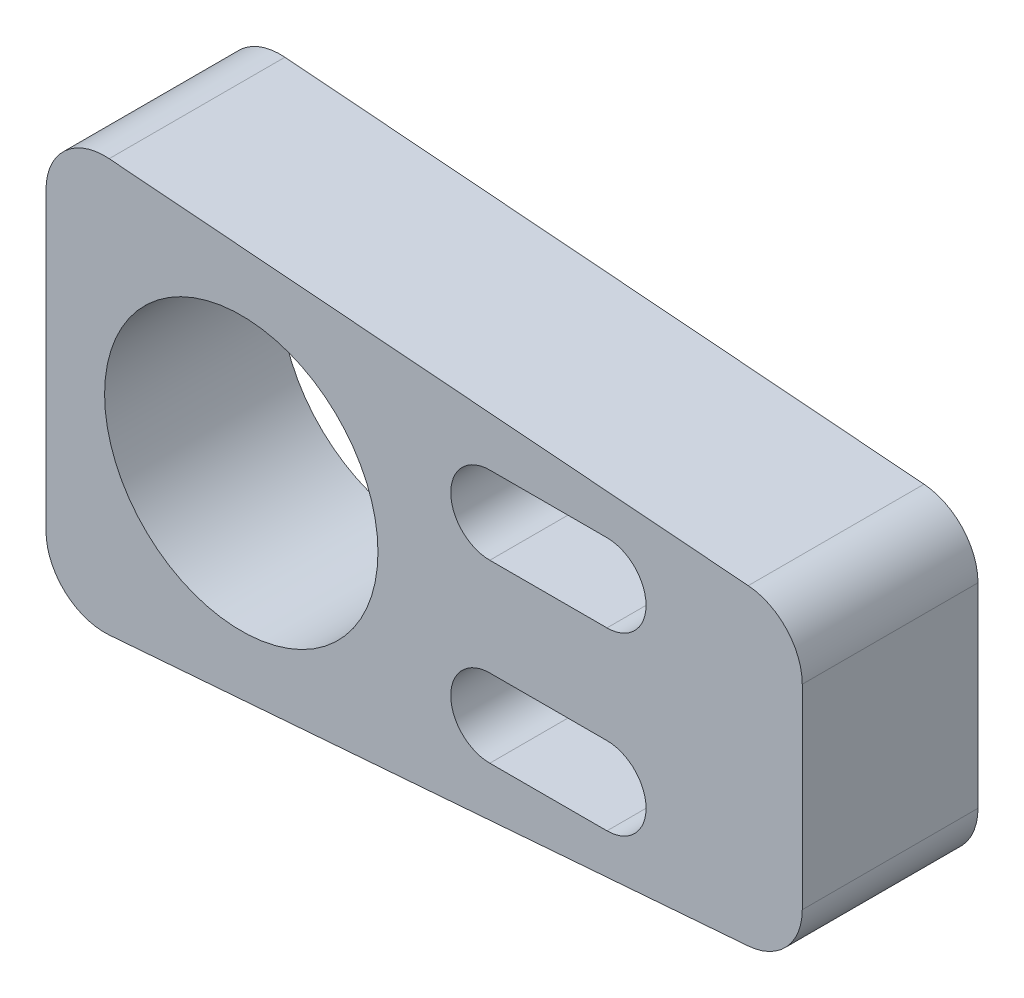
SolidWorks part; units mm, degrees
ref_plane "Front Plane" through (0, 0, 0) normal (0, 0, 1) x (1, 0, 0)
ref_plane "Top Plane" through (0, 0, 0) normal (0, 1, 0) x (1, 0, 0)
ref_plane "Right Plane" through (0, 0, 0) normal (1, 0, 0) x (0, 0, -1)
sketch "Sketch1" plane through (0, 0, 0) normal (0, 0, 1) x (1, 0, 0)
  line L1 (-114.4485, -4.5) -> (-120.4485, -4.5) construction
  line L2 (-139.9414, -10.5624) -> (-107.2135, -7.9908)
  line L3 (-143.1764, -7.5716) -> (-143.1764, 7.5716)
  line L4 (-139.9414, 10.5624) -> (-107.2135, 7.9908)
  line L5 (-104.4485, -5) -> (-104.4485, 5)
  line L8 (-114.4485, -6.5) -> (-120.4485, -6.5)
  line L9 (-114.4485, -2.5) -> (-120.4485, -2.5)
  line L10 (-114.4485, 4.5) -> (-120.4485, 4.5) construction
  line L11 (-114.4485, 2.5) -> (-120.4485, 2.5)
  line L12 (-114.4485, 6.5) -> (-120.4485, 6.5)
  arc A1 (-114.4485, -6.5) -> (-114.4485, -2.5) centre (-114.4485, -4.5) ccw
  arc A2 (-120.4485, -2.5) -> (-120.4485, -6.5) centre (-120.4485, -4.5) ccw
  arc A3 (-114.4485, 2.5) -> (-114.4485, 6.5) centre (-114.4485, 4.5) ccw
  arc A4 (-120.4485, 6.5) -> (-120.4485, 2.5) centre (-120.4485, 4.5) ccw
  circle A5 centre (-133.1764, 0) radius 7
  circle A7 centre (-133.1764, 0) radius 10
  circle A8 centre (-120.4485, 4.5) radius 3.5
  circle A9 centre (-120.4485, -4.5) radius 3.5
  arc A10 (-143.1764, 7.5716) -> (-139.9414, 10.5624) centre (-140.1764, 7.5716) cw
  arc A11 (-139.9414, -10.5624) -> (-143.1764, -7.5716) centre (-140.1764, -7.5716) cw
  arc A12 (-107.2135, -7.9908) -> (-104.4485, -5) centre (-107.4485, -5) ccw
  arc A13 (-107.2135, 7.9908) -> (-104.4485, 5) centre (-107.4485, 5) cw
  point P5 (-104.4485, 0)
  point P12 (-117.4485, -4.5)
  point P17 (-117.4485, 4.5)
  dimension "D1" = 20
  dimension "D2" = 1.5
  dimension "D4" = 3
  dimension "D5" = 2
  dimension "D7" = 10
  dimension "D8" = 14
  dimension "D3" = 6
  dimension "D6" = 10
extrude "Boss-Extrude1" add sketch "Sketch1" along normal blind 9 contours L12 A8 L11 A4 | A7 | A10 L3 A7 L4 | A11 L2 A7 L3 | A9 A7 L2 | L9 A9 L8 A2
